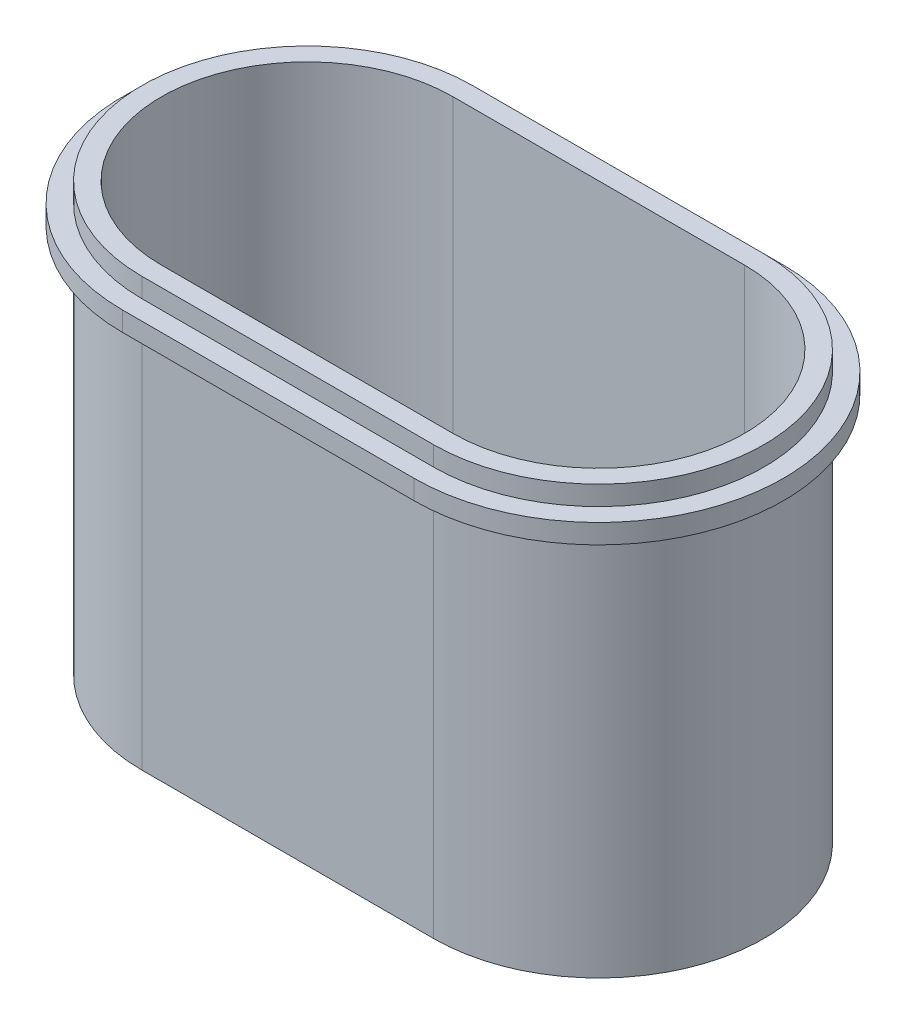
SolidWorks part; units mm, degrees
material "灰铸铁"
ref_plane "前视基准面" through (0, 0, 0) normal (0, 0, 1) x (1, 0, 0)
ref_plane "上视基准面" through (0, 0, 0) normal (0, 1, 0) x (1, 0, 0)
ref_plane "右视基准面" through (0, 0, 0) normal (1, 0, 0) x (0, 0, -1)
sketch "草图1" plane through (0, 0, 0) normal (0, 1, 0) x (1, 0, 0)
  line L1 (-75, 95) -> (75, 95)
  line L3 (-75, -95) -> (75, -95)
  line L5 (-75, 95) -> (75, -95) construction
  line L6 (-75, -95) -> (75, 95) construction
  arc A0 (-75, 95) -> (-75, -95) centre (-75, 0) ccw
  arc A1 (75, -95) -> (75, 95) centre (75, 0) ccw
  point P0 (0, 0)
  point P10 (72.635, -95)
  dimension "D3" = 95
  dimension "D4" = 95
  dimension "D1" = 150
  dimension "D2" = 95
  dimension "D5" = 190
  dimension "D6" = 75
extrude "凸台-拉伸1" add sketch "草图1" along normal blind 10
sketch "草图2" plane through (0, 10, 0) normal (0, 1, 0) x (1, 0, 0)
  line L1 (-75, 85) -> (75, 85)
  line L3 (-75, -85) -> (75, -85)
  line L5 (-75, 85) -> (75, -85) construction
  line L6 (-75, -85) -> (75, 85) construction
  arc A0 (-75, 85) -> (-75, -85) centre (-75, 0) ccw
  arc A2 (75, -85) -> (75, 85) centre (75, 0) ccw
  point P0 (0, 0)
  dimension "D5" = 85
  dimension "D6" = 85
  dimension "D1" = 150
  dimension "D2" = 170
  dimension "D3" = 85
  dimension "D4" = 75
extrude "凸台-拉伸2" add sketch "草图2" along normal blind 10
sketch "草图3" plane through (0, 0, 0) normal (0, -1, 0) x (1, 0, 0)
  line L2 (-75, -85) -> (75, -85)
  line L3 (75, 85) -> (-75, 85)
  line L4 (-75, -85) -> (75, -85)
  line L5 (75, 85) -> (-75, 85)
  arc A2 (75, -85) -> (75, 85) centre (75, 0) ccw
  arc A3 (-75, 85) -> (-75, -85) centre (-75, 0) ccw
  arc A4 (75, -85) -> (75, 85) centre (75, 0) ccw
  arc A5 (-75, 85) -> (-75, -85) centre (-75, 0) ccw
  dimension "D1" = 0
extrude "凸台-拉伸3" add sketch "草图3" along normal blind 200
sketch "草图4" plane through (0, 20, 0) normal (0, 1, 0) x (1, 0, 0)
  line L1 (-75, 75) -> (75, 75)
  line L3 (-75, -75) -> (75, -75)
  line L5 (-75, 75) -> (75, -75) construction
  line L6 (-75, -75) -> (75, 75) construction
  arc A0 (-75, 75) -> (-75, -75) centre (-75, 0) ccw
  arc A1 (75, -75) -> (75, 75) centre (75, 0) ccw
  point P1 (0, 0)
  dimension "D5" = 75
  dimension "D6" = 75
  dimension "D1" = 150
  dimension "D2" = 150
  dimension "D3" = 75
  dimension "D4" = 75
extrude "切除-拉伸1" cut sketch "草图4" against normal through all
